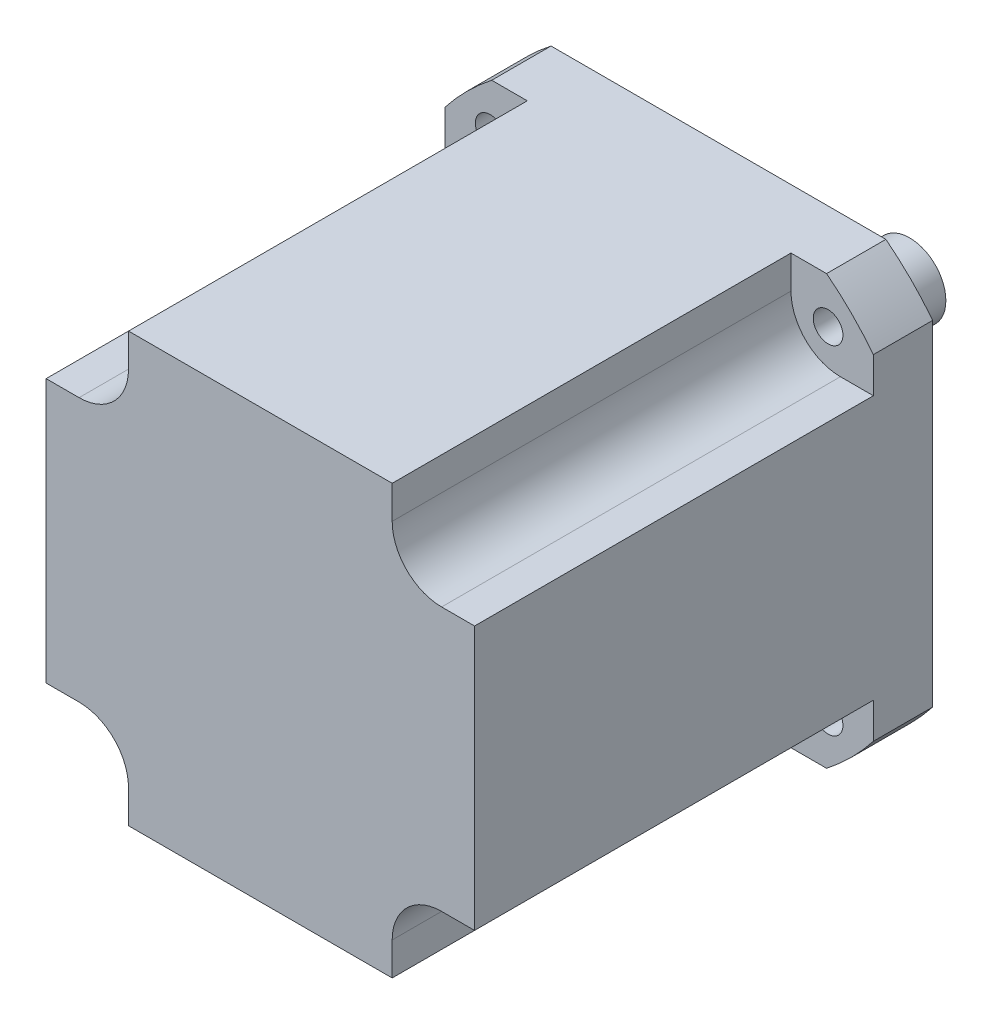
SolidWorks part; units mm, degrees
ref_plane "前视基准面" through (0, 0, 0) normal (0, 0, 1) x (1, 0, 0)
ref_plane "上视基准面" through (0, 0, 0) normal (0, 1, 0) x (1, 0, 0)
ref_plane "右视基准面" through (0, 0, 0) normal (1, 0, 0) x (0, 0, -1)
sketch "草图1" plane through (0, 0, 0) normal (0, 0, 1) x (1, 0, 0)
  line L1 (0, 0) -> (130, 0)
  line L2 (0, 0) -> (0, -130)
  line L3 (0, -130) -> (130, -130)
  line L4 (130, 0) -> (130, -130)
  dimension "D1" = 130
  dimension "D2" = 130
extrude "拉伸1" add sketch "草图1" along normal blind 139
sketch "草图2" plane through (0, 0, 0) normal (0, 0, -1) x (-1, 0, 0)
  line L0 (-130, 0) -> (0, 0) construction
  line L1 (-130, -130) -> (-130, 0) construction
  circle A0 centre (-65, -65) radius 55
  dimension "D1" = 110
  dimension "D2" = 65
  dimension "D3" = 65
extrude "拉伸2" add sketch "草图2" along normal blind 6
sketch "草图3" plane through (0, 0, -6) normal (0, 0, -1) x (-1, 0, 0)
  circle A0 centre (-65, -65) radius 11
  dimension "D1" = 22
extrude "拉伸3" add sketch "草图3" along normal blind 52
sketch "草图5" plane through (0, 0, 0) normal (0, 0, -1) x (-1, 0, 0)
  circle A2 centre (-13.7348, -13.7348) radius 4.5
  circle A3 centre (-13.7348, -116.2652) radius 4.5
  circle A4 centre (-116.2652, -116.2652) radius 4.5
  circle A5 centre (-116.2652, -13.7348) radius 4.5
extrude "切除-拉伸2" cut sketch "草图5" against normal blind 137
ref_plane "基准面1" through (0, 0, 18) normal (0, 0, -1) x (-1, 0, 0)
sketch "草图7" plane through (0, 0, 18) normal (0, 0, -1) x (-1, 0, 0)
  line L2 (-130, 0) -> (-105, 0)
  line L3 (-105, 0) -> (-105, -10)
  line L4 (-130, -25) -> (-120, -25)
  line L5 (-130, 0) -> (-130, -25)
  line L6 (0, 0) -> (0, -25)
  line L7 (0, -25) -> (-10, -25)
  line L8 (-25, 0) -> (-25, -10)
  line L9 (0, 0) -> (-25, 0)
  line L11 (0, -130) -> (-25, -130)
  line L12 (-25, -130) -> (-25, -120)
  line L13 (0, -105) -> (-10, -105)
  line L14 (0, -130) -> (0, -105)
  line L15 (-130, -130) -> (-130, -105)
  line L16 (-130, -105) -> (-120, -105)
  line L17 (-105, -130) -> (-105, -120)
  line L18 (-130, -130) -> (-105, -130)
  arc A0 (-25, -10) -> (-10, -25) centre (-10, -10) ccw
  arc A1 (-105, -10) -> (-120, -25) centre (-120, -10) cw
  arc A2 (-105, -120) -> (-120, -105) centre (-120, -120) ccw
  arc A3 (-25, -120) -> (-10, -105) centre (-10, -120) cw
  dimension "D1" = 25
  dimension "D2" = 25
extrude "切除-拉伸5" cut sketch "草图7" against normal through all
sketch "草图10" plane through (0, 0, 0) normal (0, 0, -1) x (-1, 0, 0)
  circle A0 centre (-65, -65) radius 82.5
  dimension "D1" = 165
extrude "切除-拉伸6" cut sketch "草图10" against normal through all flip side to cut
